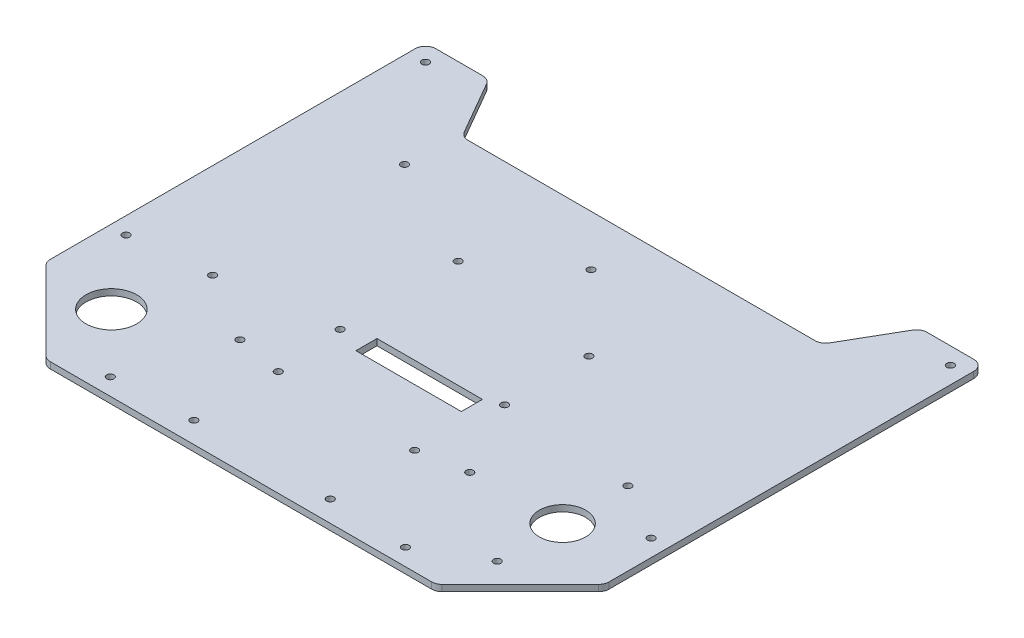
SolidWorks part; units mm, degrees
material "Acier non allié"
ref_plane "Front" through (0, 0, 0) normal (0, 0, 1) x (1, 0, 0)
ref_plane "Top" through (0, 0, 0) normal (0, 1, 0) x (1, 0, 0)
ref_plane "Right" through (0, 0, 0) normal (1, 0, 0) x (0, 0, -1)
sketch "Esquisse1" plane through (0, 0, 0) normal (0, 1, 0) x (1, 0, 0)
  line L0 (0, 0) -> (0, 1919.0564) construction
  line L1 (-92.5, 0) -> (92.5, 0)
  line L2 (92.5, 0) -> (132.5, 40)
  line L3 (132.5, 40) -> (132.5, 220)
  line L4 (132.5, 220) -> (102.5, 220)
  line L5 (102.5, 220) -> (85.1795, 190)
  line L6 (85.1795, 190) -> (-85.1795, 190)
  line L7 (-102.5, 220) -> (-85.1795, 190)
  line L8 (-132.5, 220) -> (-102.5, 220)
  line L9 (-132.5, 40) -> (-132.5, 220)
  line L10 (-92.5, 0) -> (-132.5, 40)
  point P12 (0, 190)
  dimension "D1" = 132.5
  dimension "D2" = 220
  dimension "D3" = 30
  dimension "D4" = 30
  dimension "D5" = 40
  dimension "D6" = 40
  dimension "D7" = 60
extrude "Boss.-Extru.1" add sketch "Esquisse1" along normal blind 3
fillet "Congé1" radius 5 10 edges at (132.5, 1.5, -220) (102.5, 1.5, -220) (85.1795, 1.5, -190) (-85.1795, 1.5, -190) (-102.5, 1.5, -220) (-132.5, 1.5, -220) (-132.5, 1.5, -40) (-92.5, 1.5, 0) (92.5, 1.5, 0) (132.5, 1.5, -40)
sketch "Esquisse2" plane through (0, 0, 0) normal (0, -1, 0) x (1, 0, 0)
  line L0 (0, 0) -> (0, -330.9968) construction
  line L1 (-90.4289, 0) -> (90.4289, 0) construction
  line L2 (-105.3868, -220) -> (-127.5, -220) construction
  line L3 (-132.5, -215) -> (-132.5, -42.0711) construction
  circle A0 centre (-70, -8) radius 1
  circle A1 centre (-124.5, -70) radius 1
  circle A2 centre (-124.5, -212) radius 1
  circle A3 centre (124.5, -212) radius 1
  circle A4 centre (124.5, -70) radius 1
  circle A5 centre (70, -8) radius 1
  dimension "D3" = 2
  dimension "D6" = 2
  dimension "D9" = 2
  dimension "D1" = 70
  dimension "D2" = 8
  dimension "D4" = 124.5
  dimension "D5" = 70
  dimension "D7" = 8
  dimension "D8" = 8
extrude "Enlèv. mat.-Extru.1" cut sketch "Esquisse2" against normal through all
hole_wizard "Dégagement M31" positions "Esquisse3" profile "Esquisse4" hole size "M3" standard "ISO" end condition through all
sketch "Esquisse3" plane through (0, 0, 0) normal (0, -1, 0) x (-1, 0, 0)
  point P0 (-70, 8)
  point P3 (-124.5, 70)
  point P6 (-124.5, 212)
  point P9 (124.5, 212)
  point P12 (124.5, 70)
  point P15 (70, 8)
sketch "Esquisse4" plane through (70, 0, -8) normal (1, 0, 0) x (0, 0, -1)
  line L0 (0, 0) -> (0, 3)
  line L1 (0, 3) -> (1.7, 3)
  line L2 (1.7, 3) -> (1.7, 0)
  line L5 (1.7, 0) -> (0, 0)
  line L11 (0, -6.35) -> (0, 107.95) construction
  dimension "Diamètre du perçage jusqu'au prochain" = 3.4
  dimension "Profondeur du perçage jusqu'au prochain" = 3
sketch "Esquisse5" plane through (0, 0, 0) normal (0, -1, 0) x (1, 0, 0)
  line L0 (-35, -138) -> (-35, -82) construction
  line L5 (35, -130) -> (35, -90) construction
  line L6 (132.5, -42.0711) -> (132.5, -215) construction
  line L7 (97.5, -86) -> (97.5, -24) construction
  line L20 (-132.5, -215) -> (-132.5, -42.0711) construction
  line L21 (-90.4289, 0) -> (90.4289, 0) construction
  line L22 (-105.3868, -220) -> (-127.5, -220) construction
  line L27 (-132.5, -215) -> (-132.5, -42.0711) construction
  line L28 (127.5, -220) -> (105.3868, -220) construction
  line L29 (-54.5, -54) -> (54.5, -54) construction
  line L30 (-54.5, -54) -> (-54.5, -166) construction
  line L31 (-54.5, -166) -> (54.5, -166) construction
  line L32 (54.5, -54) -> (54.5, -166) construction
  line L33 (-87.5, -74) -> (-87.5, -165) construction
  line L34 (-22.5, -87) -> (27.5, -87)
  line L35 (-22.5, -87) -> (-22.5, -77)
  line L36 (-22.5, -77) -> (27.5, -77)
  line L37 (27.5, -87) -> (27.5, -77)
  line L39 (127.5, -220) -> (105.3868, -220) construction
  line L40 (-32.335, -50) -> (32.335, -50) construction
  line L41 (-32.335, -50) -> (-32.335, -10) construction
  line L42 (-32.335, -10) -> (32.335, -10) construction
  line L43 (32.335, -50) -> (32.335, -10) construction
  circle A0 centre (-97.5, -36) radius 12
  circle A3 centre (97.5, -55) radius 11
  circle A4 centre (97.5, -86) radius 1.5
  circle A5 centre (97.5, -24) radius 1.5
  circle A6 centre (-35, -138) radius 1
  circle A7 centre (-35, -82) radius 1
  circle A8 centre (35, -130) radius 1
  circle A9 centre (35, -90) radius 1
  circle A10 centre (0, -166) radius 1.5
  circle A11 centre (-54.5, -54) radius 1.5
  circle A12 centre (54.5, -54) radius 1.5
  circle A13 centre (-87.5, -74) radius 1.5
  circle A14 centre (-87.5, -165) radius 1.5
  circle A15 centre (-32.335, -50) radius 1.5
  circle A16 centre (-32.335, -10) radius 1.5
  circle A17 centre (32.335, -10) radius 1.5
  circle A18 centre (32.335, -50) radius 1.5
  point P8 (97.5, -55)
  point P18 (-35, -110)
  point P23 (0, -166)
  point P29 (54.5, -110)
  point P47 (-22.5, -82)
  point P48 (2.5, -77)
  point P57 (0, 0)
  point P58 (0, -10)
extrude "Enlèv. mat.-Extru.2" cut sketch "Esquisse5" against normal through all
fillet "Congé2" [suppressed] radius 3
hole_wizard "Dégagement M32" positions "Esquisse6" profile "Esquisse7" hole size "M3" standard "ISO" end condition up to next
sketch "Esquisse6" plane through (0, 3, 0) normal (0, 1, 0) x (1, 0, 0)
  point P7 (97.5, 86)
  point P10 (97.5, 24)
  point P13 (-54.5, 54)
  point P16 (54.5, 54)
  point P19 (0, 166)
  point P24 (-87.5, 74)
  point P27 (-87.5, 165)
  point P30 (-32.335, 50)
  point P33 (-32.335, 10)
  point P36 (32.335, 10)
  point P39 (32.335, 50)
  point P42 (-35, 138)
  point P45 (-35, 82)
  point P48 (35, 90)
  point P51 (35, 130)
sketch "Esquisse7" plane through (97.5, 3, -86) normal (1, 0, 0) x (0, 0, 1)
  line L0 (0, 0) -> (0, 3)
  line L1 (0, 3) -> (1.7, 3)
  line L2 (1.7, 3) -> (1.7, 0)
  line L5 (1.7, 0) -> (0, 0)
  line L11 (0, -6.35) -> (0, 107.95) construction
  dimension "Diamètre du perçage jusqu'au prochain" = 3.4
  dimension "Profondeur du perçage jusqu'au prochain" = 3
hole_wizard "Dégagement M2.51" [suppressed] positions "Esquisse8" profile "Esquisse9" hole size "M2.5" standard "ISO"
sketch "Esquisse8" plane through (0, 3, 0) normal (0, 1, 0) x (1, 0, 0)
  point P0 (-35, 138)
  point P3 (-35, 82)
  point P6 (35, 90)
  point P9 (35, 130)
sketch "Esquisse9" plane through (-35, 3, -138) normal (1, 0, 0) x (0, 0, 1)
  line L0 (0, 0) -> (0, 3)
  line L1 (0, 3) -> (1.45, 3)
  line L2 (1.45, 3) -> (1.45, 0)
  line L5 (1.45, 0) -> (0, 0)
  line L11 (0, -6.35) -> (0, 107.95) construction
  dimension "Diamètre du perçage jusqu'au prochain" = 2.9
  dimension "Profondeur du perçage jusqu'au prochain" = 3
sketch "Esquisse10" plane through (0, 3, 0) normal (0, 1, 0) x (1, 0, 0)
  line L3 (-57.5, 38) -> (57.5, 38) construction
  line L4 (-132.5, 215) -> (-132.5, 42.0711) construction
  line L5 (132.5, 42.0711) -> (132.5, 215) construction
  line L6 (-90.4289, 0) -> (90.4289, 0) construction
  text T0 "TUTANKHABOT"
  text T1 "\r\nDesigned and assembled by :\r\n" font "Century Gothic" height in points 14
  text T2 "\r\n\r\nBERNARD Théau\r\nBOSSCHAERT Sébastien\r\nBOULANGER François\r\n" font "Century Gothic" height in points 14
  text T3 "\r\n\r\nISENGUERRE Nicolas\r\nLANNOEY Diego\r\nMERCIER Clément" font "Century Gothic" height in points 14
  dimension "D1" = 75
  dimension "D2" = 75
  dimension "D3" = 38
extrude "Enlèv. mat.-Extru.3" [suppressed] cut sketch "Esquisse10" against normal blind 0.1
equation "\"WIDTH\"= 300mm'Total width of the robot"
equation "\"LENGTH\"= 220mm'Total length of the robot"
equation "\"CUT_DEPTH\"= 45mm'Depth of the cut on the edges of the plate"
equation "\"Plate_th\"= 3mm'Thickness of the plate"
equation "\"D1\"= \"Plate_th\""
equation "\"D23@Esquisse5\"=(265-70)/2"
